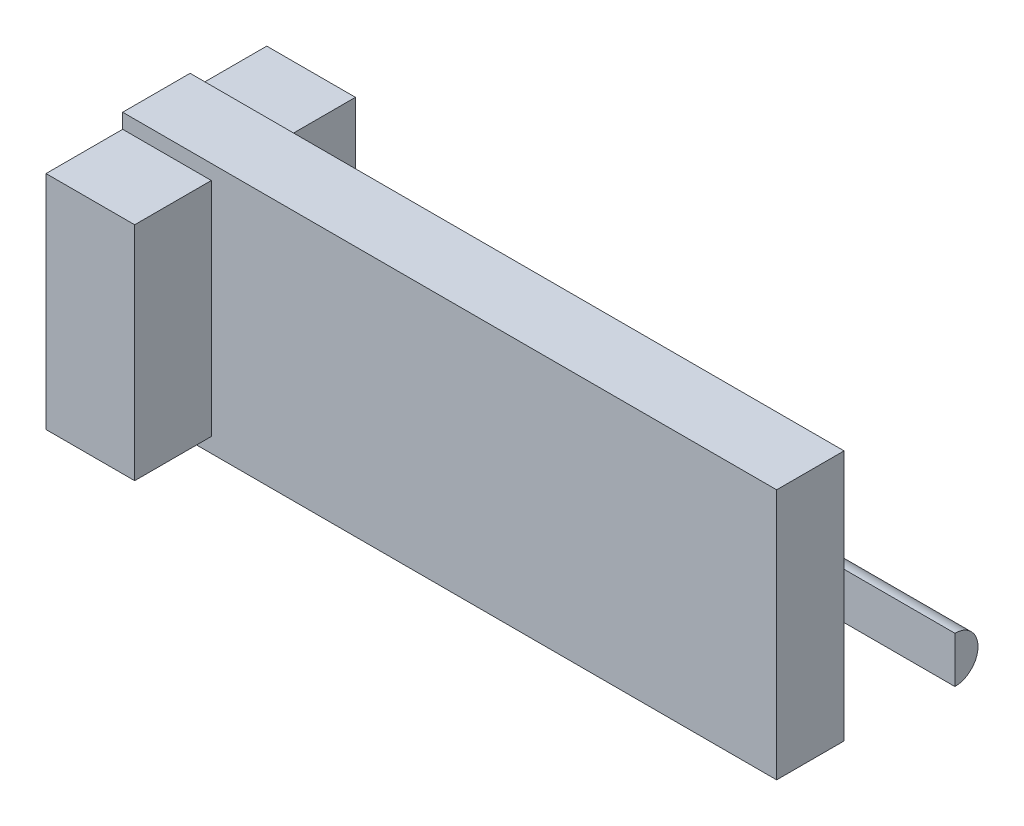
SolidWorks part; units mm, degrees
ref_plane "Front Plane" through (0, 0, 0) normal (0, 0, 1) x (1, 0, 0)
ref_plane "Top Plane" through (0, 0, 0) normal (0, 1, 0) x (1, 0, 0)
ref_plane "Right Plane" through (0, 0, 0) normal (1, 0, 0) x (0, 0, -1)
sketch "Sketch1" plane through (0, 0, 0) normal (0, 0, 1) x (1, 0, 0)
  line L1 (-17.7, 6.8) -> (17.7, 6.8)
  line L2 (-17.7, 6.8) -> (-17.7, -6.8)
  line L3 (-17.7, -6.8) -> (17.7, -6.8)
  line L4 (17.7, 6.8) -> (17.7, -6.8)
  line L5 (-17.7, 6.8) -> (17.7, -6.8) construction
  line L6 (-17.7, -6.8) -> (17.7, 6.8) construction
  point P0 (0, 0)
  dimension "D1" = 13.6
  dimension "D2" = 35.4
extrude "Boss-Extrude1" add sketch "Sketch1" along normal mid plane 3.65
sketch "Sketch2" plane through (0, 0, 1.825) normal (0, 0, 1) x (1, 0, 0)
  line L0 (0, 0) -> (-17.7, 0) construction
  line L1 (-17.7, 6) -> (-12.9, 6)
  line L2 (-17.7, 6) -> (-17.7, -6)
  line L3 (-17.7, -6) -> (-12.9, -6)
  line L4 (-12.9, 6) -> (-12.9, -6)
  line L5 (-17.7, 6) -> (-12.9, -6) construction
  line L6 (-17.7, -6) -> (-12.9, 6) construction
  line L7 (-17.7, 6.8) -> (-17.7, -6.8) construction
  point P0 (-15.3, 0)
  point P10 (-14.465, 0)
  dimension "D1" = 4.8
  dimension "D2" = 12
extrude "Boss-Extrude2" add sketch "Sketch2" along normal blind 4.15
sketch "Sketch3" plane through (0, 0, -1.825) normal (0, 0, -1) x (-1, 0, 0)
  line L4 (17.7, 6) -> (12.9, 6)
  line L5 (12.9, 6) -> (12.9, -6)
  line L6 (12.9, -6) -> (17.7, -6)
  line L7 (17.7, -6) -> (17.7, 6)
  line L8 (17.7, 6) -> (12.9, 6)
  line L9 (12.9, 6) -> (12.9, -6)
  line L10 (12.9, -6) -> (17.7, -6)
  line L11 (17.7, -6) -> (17.7, 6)
  dimension "D1" = 0
extrude "Boss-Extrude3" add sketch "Sketch3" along normal blind 4.15
sketch "Sketch4" plane through (0, 0, -1.825) normal (0, 0, -1) x (-1, 0, 0)
  line L0 (0, 0) -> (-17.7, 0) construction
  line L1 (-17.7, -6.8) -> (-17.7, 6.8) construction
  line L2 (-11.7, 0) -> (-23.7, 0)
  line L3 (-23.7, 1.25) -> (-11.7, 1.25)
  line L4 (-23.7, 1.25) -> (-23.7, -1.25)
  line L5 (-23.7, -1.25) -> (-11.7, -1.25)
  line L6 (-11.7, 1.25) -> (-11.7, -1.25)
  line L7 (-23.7, 1.25) -> (-11.7, -1.25) construction
  line L8 (-23.7, -1.25) -> (-11.7, 1.25) construction
  dimension "D1" = 2.5
  dimension "D2" = 6
revolve "Revolve1" add sketch "Sketch4" angle 180 about L2
sketch "Sketch5" plane through (0, 0, 0) normal (0, 0, 1) x (1, 0, 0)
  point P0 (0, 0)
